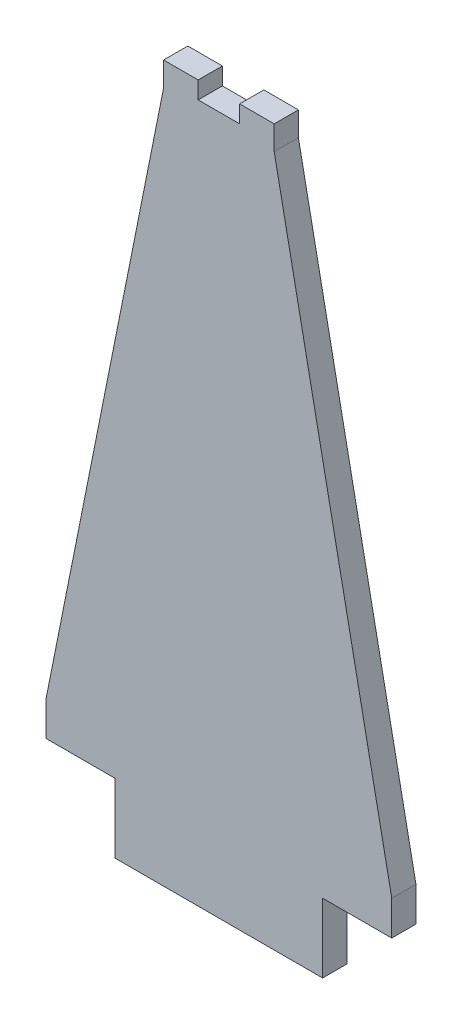
SolidWorks part; units mm, degrees
material "PBT General Purpose"
ref_plane "Front Plane" through (0, 0, 0) normal (0, 0, 1) x (1, 0, 0)
ref_plane "Top Plane" through (0, 0, 0) normal (0, 1, 0) x (1, 0, 0)
ref_plane "Right Plane" through (0, 0, 0) normal (1, 0, 0) x (0, 0, -1)
sketch "frame_outline" plane through (0, 0, 0) normal (0, 0, 1) x (1, 0, 0)
  line L110 (0, 0) -> (3, 0)
  line L117 (3, 0) -> (3, 1)
  line L118 (3, 1) -> (4, 1)
  line L119 (4, 1) -> (4, 1.5)
  line L120 (4, 1.5) -> (2.3, 10)
  line L121 (2.3, 10) -> (2.3, 10.35)
  line L122 (2.3, 10.35) -> (1.8, 10.35)
  line L123 (1.8, 10.35) -> (1.8, 10.1)
  line L124 (1.8, 10.1) -> (1.2, 10.1)
  line L125 (1.2, 10.1) -> (1.2, 10.35)
  line L126 (1.2, 10.35) -> (0.7, 10.35)
  line L127 (0.7, 10.35) -> (0.7, 10)
  line L128 (0.7, 10) -> (-1, 1.5)
  line L129 (-1, 1.5) -> (-1, 1)
  line L130 (-1, 1) -> (0, 1)
  line L131 (0, 1) -> (0, 0)
  line L132 (1.5, 10.1) -> (1.5, 0) construction
  dimension "D1" = 5
  dimension "D2" = 3
  dimension "D3" = 1
  dimension "D4" = 0.5
  dimension "D5" = 9
  dimension "D6" = 0.6
  dimension "D7" = 0.25
  dimension "D8" = 0.5
  dimension "D9" = 0.1
extrude "Boss-Extrude1" add sketch "frame_outline" along normal mid plane 0.35
equation "\"t\"= 0.25'thickness of the sheets"
equation "\"t_cf\" = 0.115'thickness of single carbon fiber layer"
equation "\"t_kapton\" = 0.025'thickness of single Kapton flex layer"
equation "\"t_fr4\" = 0.1'thickness of FR4 with copper layer"
equation "\"joint_flex\"= 0.1'Width of flextures gap"
equation "\"joint_flex_eff\"= 0.02'Width of flecture after castelation"
equation "\"joint_fold\"= 0.2'Width of folding joints for 90deg fold"
equation "\"gap_tolerance\"= 0.002'Width to have interfecence fit between carbon fiber inserts"
equation "\"assemble_angle\"= 90'Angle of assembly parts"
equation "\"D1@Boss-Extrude1\"=0.35"
equation "\"link_lift\"= 0.5'Actuation linkage amplification for the lift motion"
equation "\"link_swing\"= 0.45'Actuation linkage amplification for the swing motion"
